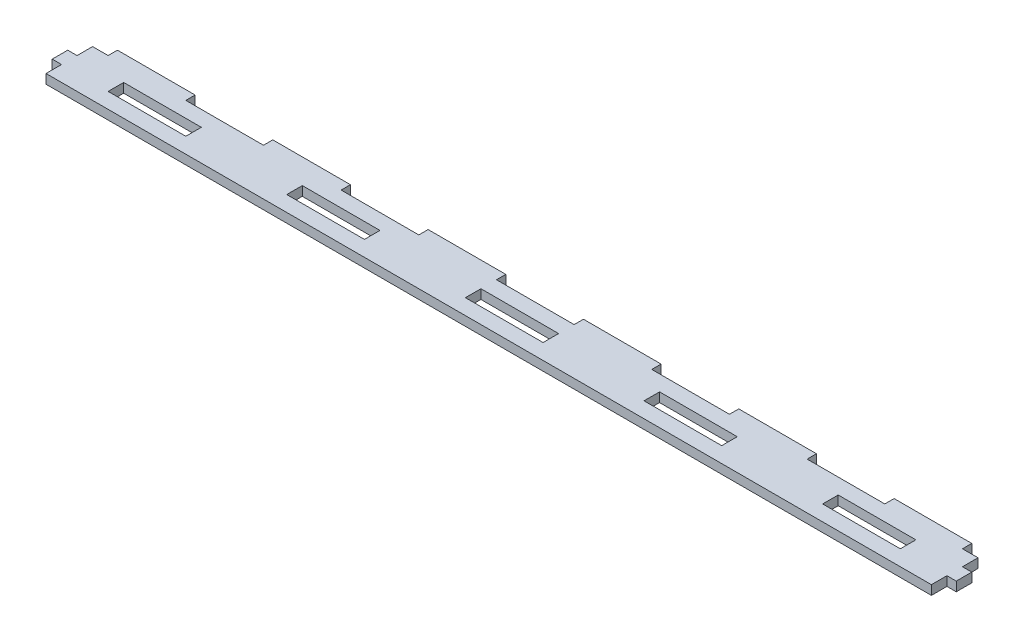
SolidWorks part; units mm, degrees
material "Buk"
ref_plane "Přední rovina" through (0, 0, 0) normal (0, 0, 1) x (1, 0, 0)
ref_plane "Horní rovina" through (0, 0, 0) normal (0, 1, 0) x (1, 0, 0)
ref_plane "Pravá rovina" through (0, 0, 0) normal (1, 0, 0) x (0, 0, -1)
sketch "Skica1" plane through (0, 0, 0) normal (0, 1, 0) x (1, 0, 0)
  line L1 (0, 15) -> (285, 15)
  line L2 (0, 15) -> (0, 0)
  line L3 (0, 0) -> (285, 0)
  line L4 (285, 15) -> (285, 0)
  dimension "D1" = 285
  dimension "D2" = 15
extrude "Přidat vysunutím1" add sketch "Skica1" along normal blind 3
sketch "Skica2" plane through (0, 0, 0) normal (0, 1, 0) x (1, 0, 0)
  line L0 (55, 15) -> (80, 15)
  line L1 (0, 10) -> (-3, 10)
  line L2 (0, 10) -> (0, 5)
  line L3 (0, 5) -> (-3, 5)
  line L4 (-3, 10) -> (-3, 5)
  line L5 (0, 15) -> (0, 0) construction
  line L6 (55, 15) -> (55, 18)
  line L7 (5, 15) -> (30, 15)
  line L8 (5, 15) -> (5, 18)
  line L9 (5, 18) -> (30, 18)
  line L10 (30, 15) -> (30, 18)
  line L11 (55, 18) -> (80, 18)
  line L12 (80, 15) -> (80, 18)
  line L13 (105, 15) -> (130, 15)
  line L14 (105, 15) -> (105, 18)
  line L15 (142.5, 15) -> (142.5, 0) construction
  line L16 (285, 15) -> (0, 15) construction
  line L17 (105, 18) -> (130, 18)
  line L18 (0, 0) -> (285, 0) construction
  line L19 (130, 15) -> (130, 18)
  line L20 (155, 15) -> (180, 15)
  line L21 (155, 15) -> (155, 18)
  line L22 (155, 18) -> (180, 18)
  line L23 (180, 15) -> (180, 18)
  line L24 (288, 10) -> (288, 5)
  line L25 (285, 5) -> (288, 5)
  line L26 (285, 10) -> (285, 5)
  line L27 (285, 10) -> (288, 10)
  line L28 (205, 15) -> (230, 15)
  line L29 (205, 15) -> (205, 18)
  line L30 (205, 18) -> (230, 18)
  line L31 (230, 15) -> (230, 18)
  line L32 (255, 15) -> (280, 15)
  line L33 (255, 15) -> (255, 18)
  line L34 (255, 18) -> (280, 18)
  line L35 (280, 15) -> (280, 18)
  line L36 (30, 18) -> (55, 18) construction
  line L37 (55, 18) -> (62.3133, 17.7051) construction
  dimension "D1" = 5
  dimension "D2" = 3
  dimension "D3" = 5
  dimension "D4" = 6
  dimension "D5" = 25
extrude "Přidat vysunutím2" add sketch "Skica2" along normal up to surface (3 mm away) up to face at (142.5, 3, -7.5)
sketch "Skica3" plane through (0, 0, 0) normal (0, 1, 0) x (1, 0, 0)
  line L0 (0, 0) -> (285, 0) construction
  line L1 (15, 10) -> (40, 10)
  line L2 (15, 10) -> (15, 5)
  line L3 (15, 5) -> (40, 5)
  line L4 (40, 10) -> (40, 5)
  line L5 (0, 5) -> (0, 0) construction
  line L6 (72.5, 10) -> (97.5, 10)
  line L7 (72.5, 10) -> (72.5, 5)
  line L8 (72.5, 5) -> (97.5, 5)
  line L9 (97.5, 10) -> (97.5, 5)
  line L10 (130, 10) -> (155, 10)
  line L11 (130, 10) -> (130, 5)
  line L12 (130, 5) -> (155, 5)
  line L13 (155, 10) -> (155, 5)
  line L14 (187.5, 10) -> (212.5, 10)
  line L15 (187.5, 10) -> (187.5, 5)
  line L16 (187.5, 5) -> (212.5, 5)
  line L17 (212.5, 10) -> (212.5, 5)
  line L18 (245, 10) -> (270, 10)
  line L19 (245, 10) -> (245, 5)
  line L20 (245, 5) -> (270, 5)
  line L21 (270, 10) -> (270, 5)
  line L22 (15, 10) -> (72.5, 10) construction
  line L23 (285, 0) -> (285, 5) construction
  line L25 (5, 15) -> (0, 15) construction
  dimension "D1" = 5
  dimension "D2" = 5
  dimension "D3" = 15
  dimension "D4" = 25
  dimension "D6" = 15
  dimension "D5" = 5
extrude "Odebrat vysunutím1" cut sketch "Skica3" along normal through all
